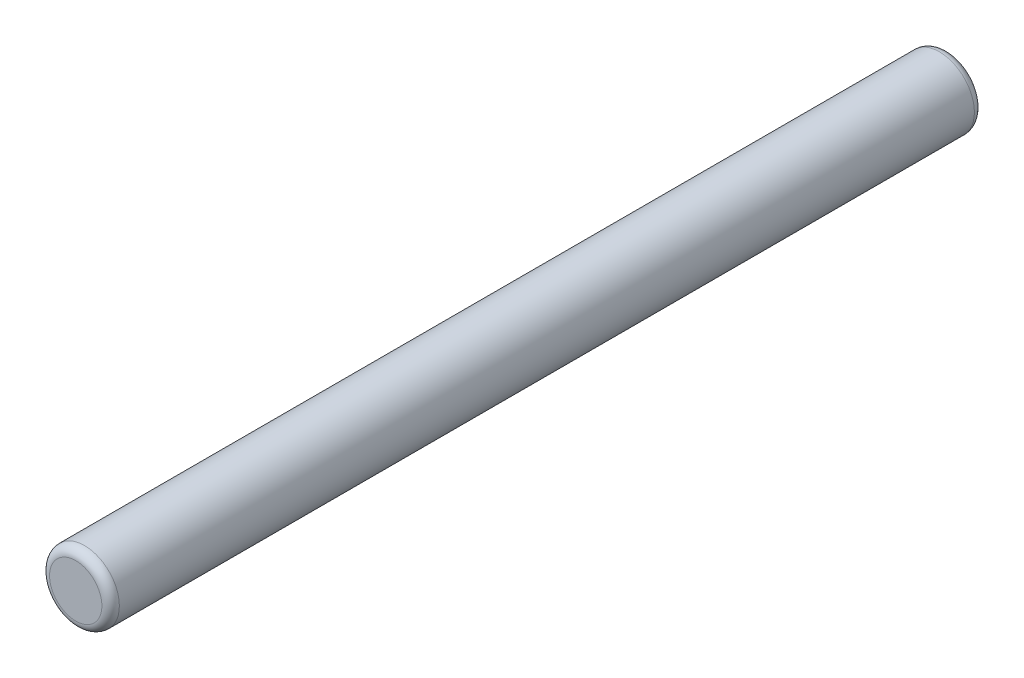
SolidWorks part; units mm, degrees
ref_plane "Front Plane" through (0, 0, 0) normal (0, 0, 1) x (1, 0, 0)
ref_plane "Top Plane" through (0, 0, 0) normal (0, 1, 0) x (1, 0, 0)
ref_plane "Right Plane" through (0, 0, 0) normal (1, 0, 0) x (0, 0, -1)
sketch "Sketch1" plane through (0, 0, 0) normal (0, 0, 1) x (1, 0, 0)
  circle A0 centre (0, 0) radius 4
  dimension "D1" = 8
extrude "Boss-Extrude1" add sketch "Sketch1" along normal blind 100
fillet "Fillet1" radius 1 2 edges at (4, 0, 100) (4, 0, 0)
